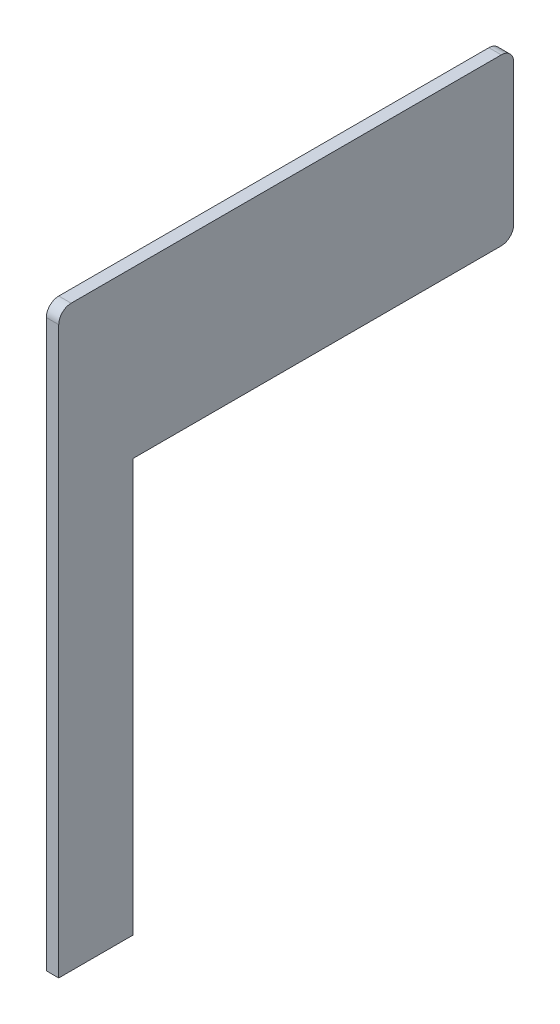
SolidWorks part; units mm, degrees
ref_plane "前视基准面" through (0, 0, 0) normal (0, 0, 1) x (1, 0, 0)
ref_plane "上视基准面" through (0, 0, 0) normal (0, 1, 0) x (1, 0, 0)
ref_plane "右视基准面" through (0, 0, 0) normal (1, 0, 0) x (0, 0, -1)
sketch "草图1" plane through (0, 0, 0) normal (1, 0, 0) x (0, 0, -1)
  line L0 (-5.8, 0) -> (5.8, 0) construction
  line L2 (-5.5, -2) -> (-5.5, -1.5)
  line L3 (-5.5, 2) -> (5.5, 2)
  line L4 (5.5, -2) -> (5.5, -1.5)
  line L5 (-5.5, -2) -> (5.5, 2) construction
  line L6 (-5.5, 2) -> (5.5, -2) construction
  line L10 (-5.5, 1.5) -> (-5.5, 0.5)
  line L11 (0, 2) -> (0, -2) construction
  line L12 (-5.5, 1.5) -> (-5.5, 2)
  line L15 (-5.5, -1.5) -> (-5.5, -0.5)
  line L17 (5.5, 1.5) -> (5.5, 0.5)
  line L20 (5.5, -1.5) -> (5.5, -0.5)
  line L22 (5.5, 1.5) -> (5.5, 2)
  line L23 (5.5, -0.5) -> (5.5, 0.5)
  line L24 (-5.5, -0.5) -> (-5.5, 0.5)
  line L25 (-3.7, -2) -> (5.5, -2)
  line L30 (-5.5, -2) -> (-5.5, -8.98)
  line L31 (-5.5, -8.98) -> (-3.7, -8.98)
  line L32 (-3.7, -8.98) -> (-3.7, -2)
  point P0 (0, 0)
  dimension "D1" = 11
  dimension "D2" = 4
  dimension "D6" = 1.8
  dimension "D7" = 6.98
extrude "凸台-拉伸1" add sketch "草图1" along normal blind 0.3
fillet "圆角1" radius 0.3 3 edges at (0.15, -2, -5.5) (0.15, 2, -5.5) (0.15, 2, 5.5)
sketch "草图4" plane through (0, -8.98, 0) normal (0, -1, 0) x (1, 0, 0)
  line L0 (0.3, 3.7) -> (0.3, -5.2) construction
  line L1 (0, 5.5) -> (0.3, 5.5)
  line L2 (0, 5.5) -> (0, 3.7)
  line L3 (0, 3.7) -> (0.3, 3.7)
  line L4 (0.3, 5.5) -> (0.3, 3.7)
  line L5 (0.15, 3.7) -> (0.15, 5.5) construction
  line L6 (0, 4.6) -> (0.3, 4.6) construction
  line L7 (0.3, 5.5) -> (0.3, 3.7) construction
  point P264 (0.15, 4.6)
extrude "凸台-拉伸3" add sketch "草图4" along normal blind 3
